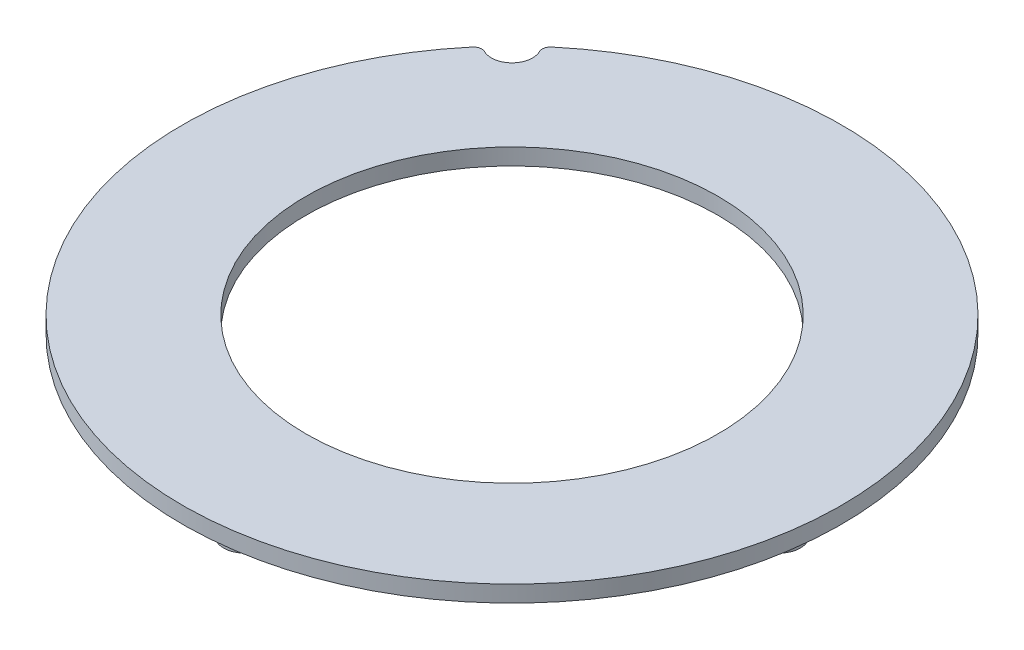
SolidWorks part; units mm, degrees
ref_plane "Front Plane" through (0, 0, 0) normal (0, 0, 1) x (1, 0, 0)
ref_plane "Top Plane" through (0, 0, 0) normal (0, 1, 0) x (1, 0, 0)
ref_plane "Right Plane" through (0, 0, 0) normal (1, 0, 0) x (0, 0, -1)
sketch "Sketch1" plane through (0, 0, 0) normal (0, 1, 0) x (1, 0, 0)
  line L0 (-1000, 0) -> (49000, 0) construction
  line L1 (0, -1000) -> (0, 49000) construction
sketch "Sketch2" plane through (0, 0, 0) normal (0, 1, 0) x (1, 0, 0)
  circle A0 centre (0, 0) radius 25
  circle A1 centre (0, 0) radius 40
  dimension "D1" = 50
  dimension "D2" = 80
extrude "Boss-Extrude2" add sketch "Sketch2" along normal blind 2
sketch "Sketch4" plane through (0, 0, 0) normal (0, -1, 0) x (1, 0, 0)
  line L0 (-201000, 0) -> (249000, 0) construction
  line L1 (0, 201000) -> (0, -249000) construction
  circle A0 centre (0, -32.5) radius 2.5
  circle A1 centre (32.5, 0) radius 2.5
  circle A2 centre (0, 32.5) radius 2.5
  circle A3 centre (-32.5, 0) radius 2.5
  dimension "D2" = 5
  dimension "D4" = 5
  dimension "D6" = 5
  dimension "D8" = 5
  dimension "D1" = 32.5
  dimension "D3" = 32.5
  dimension "D5" = 32.5
  dimension "D7" = 32.5
extrude "Boss-Extrude3" add sketch "Sketch4" along normal blind 5
sketch "Sketch5" plane through (0, 2, 0) normal (0, 1, 0) x (1, 0, 0)
  line L0 (-1000, 0) -> (49000, 0) construction
  line L1 (0, -1000) -> (0, 49000) construction
  line L2 (0, 0) -> (-35355.3391, 35355.3391) construction
  circle A0 centre (-28.2843, 28.2843) radius 2.5
  dimension "D1" = 45
  dimension "D2" = 40
  dimension "D3" = 5
extrude "Cut-Extrude1" cut sketch "Sketch5" against normal blind 10 contours A0
fillet "Fillet1" radius 1 1 edges at (-26.4621, 1, -29.9959)
fillet "Fillet2" radius 1 1 edges at (-29.9959, 1, -26.4621)
